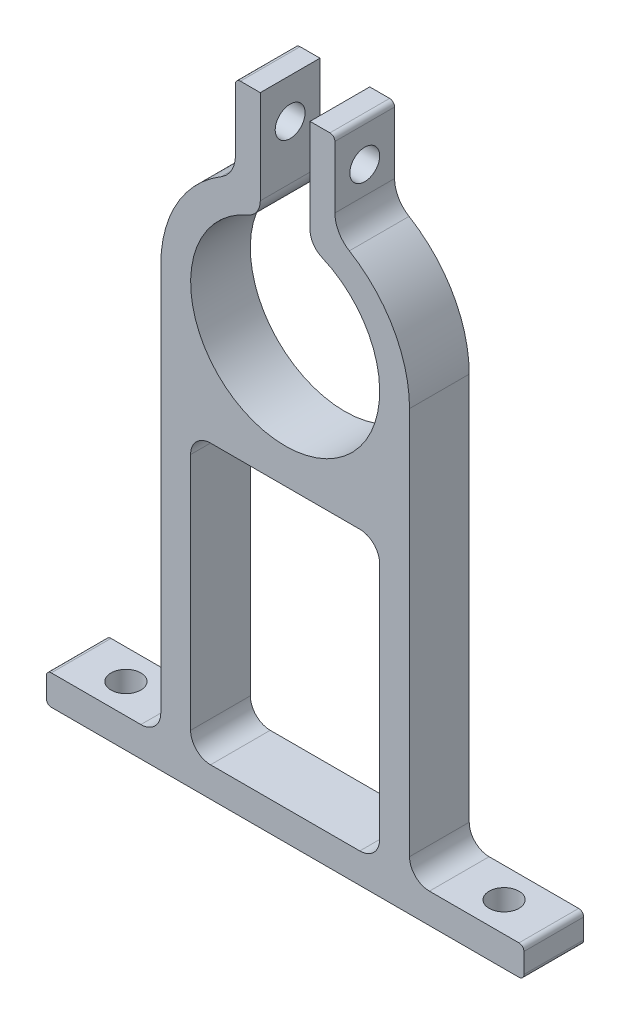
SolidWorks part; units mm, degrees
ref_plane "前视基准面" through (0, 0, 0) normal (0, 0, 1) x (1, 0, 0)
ref_plane "上视基准面" through (0, 0, 0) normal (0, 1, 0) x (1, 0, 0)
ref_plane "右视基准面" through (0, 0, 0) normal (1, 0, 0) x (0, 0, -1)
sketch "草图1" plane through (0, 0, 0) normal (0, 0, 1) x (1, 0, 0)
  line L0 (-25.6507, 0) -> (43.9949, 0) construction
  line L1 (0, 0) -> (0, 81.8893) construction
  line L2 (12.5, 3) -> (24, 3)
  line L4 (-12.5, 3) -> (-12.5, 44)
  line L6 (12.5, 3) -> (12.5, 44)
  line L7 (-24, 0) -> (24, 0)
  line L8 (-24, 0) -> (-24, 3)
  line L9 (-24, 3) -> (-12.5, 3)
  line L10 (24, 0) -> (24, 3)
  line L11 (2.5, 64) -> (5, 64)
  line L12 (-2.5, 53.1652) -> (-2.5, 64)
  line L14 (2.5, 53.1652) -> (2.5, 64)
  line L16 (-5, 55.4564) -> (-5, 64)
  line L17 (-5, 64) -> (-2.5, 64)
  line L18 (5, 55.4564) -> (5, 64)
  arc A0 (-2.5, 53.1652) -> (2.5, 53.1652) centre (0, 44) ccw
  arc A1 (12.5, 44) -> (5, 55.4564) centre (0, 44) ccw
  arc A2 (-5, 55.4564) -> (-12.5, 44) centre (0, 44) ccw
  dimension "D1" = 19
  dimension "D2" = 24
  dimension "D3" = 44
  dimension "D4" = 24
  dimension "D5" = 3
  dimension "D6" = 20
  dimension "D8" = 25
  dimension "D9" = 48
  dimension "D11" = 5
  dimension "D12" = 10
extrude "凸台-拉伸1" add sketch "草图1" along normal blind 6
sketch "草图2" plane through (0, 0, 6) normal (0, 0, 1) x (1, 0, 0)
  line L1 (-9.5, 31) -> (9.5, 31)
  line L2 (-9.5, 31) -> (-9.5, 3)
  line L3 (-9.5, 3) -> (9.5, 3)
  line L4 (9.5, 31) -> (9.5, 3)
  line L5 (-12.5, 44) -> (-12.5, 3) construction
  line L6 (12.5, 3) -> (12.5, 44) construction
  line L8 (-24, 0) -> (24, 0) construction
  arc A0 (-2.5, 53.1652) -> (2.5, 53.1652) centre (0, 44) ccw construction
  dimension "D1" = 3
  dimension "D2" = 3
  dimension "D3" = 3
  dimension "D4" = 13
extrude "切除-拉伸1" cut sketch "草图2" against normal blind 6
fillet "圆角2" radius 2 4 edges at (9.5, 31, 3) (-9.5, 31, 3) (-9.5, 3, 3) (9.5, 3, 3)
fillet "圆角3" radius 2 2 edges at (12.5, 3, 3) (-12.5, 3, 3)
sketch "草图3" plane through (0, 0, 0) normal (0, -1, 0) x (1, 0, 0)
  line L0 (-24, 6) -> (-24, 0) construction
  line L1 (24, 6) -> (24, 0) construction
  circle A0 centre (-19, 3) radius 1.5
  circle A1 centre (19, 3) radius 1.5
  point P6 (-24, 3)
  point P7 (24, 3)
  dimension "D1" = 3
  dimension "D2" = 3
  dimension "D3" = 5
  dimension "D4" = 5
extrude "切除-拉伸2" cut sketch "草图3" against normal blind 6
fillet "圆角4" radius 3 2 edges at (-5, 55.4564, 3) (5, 55.4564, 3)
fillet "圆角5" radius 0.5 6 edges at (5, 64, 3) (-5, 64, 3) (-24, 0, 3) (24, 0, 3) (24, 3, 3) (-24, 3, 3)
sketch "草图4" plane through (-5, 0, 0) normal (-1, 0, 0) x (0, 0, 1)
  line L0 (0, 64) -> (6, 64) construction
  line L1 (3, 64) -> (3, 60) construction
  circle A0 centre (3, 60) radius 1.5
  dimension "D1" = 3
  dimension "D2" = 4
extrude "切除-拉伸3" cut sketch "草图4" against normal blind 14
fillet "圆角6" radius 2 2 edges at (2.5, 53.1652, 3) (-2.5, 53.1652, 3)
